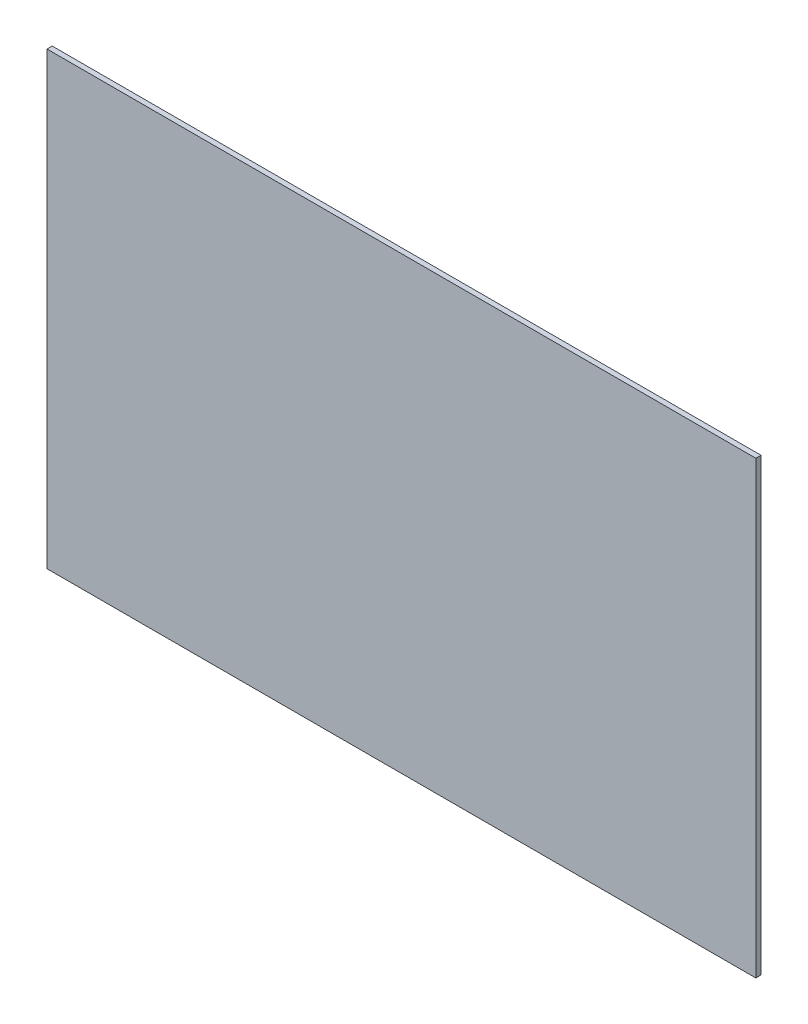
SolidWorks part; units mm, degrees
ref_plane "Plan de face" through (0, 0, 0) normal (0, 0, 1) x (1, 0, 0)
ref_plane "Plan de dessus" through (0, 0, 0) normal (0, 1, 0) x (1, 0, 0)
ref_plane "Plan de droite" through (0, 0, 0) normal (1, 0, 0) x (0, 0, -1)
sketch "Esquisse1" plane through (0, 0, 0) normal (0, 0, 1) x (1, 0, 0)
  line L1 (-274, -174) -> (274, -174)
  line L2 (-274, -174) -> (-274, 174)
  line L3 (-274, 174) -> (274, 174)
  line L4 (274, -174) -> (274, 174)
  line L5 (-274, -174) -> (274, 174) construction
  line L6 (-274, 174) -> (274, -174) construction
  point P0 (0, 0)
  dimension "D1" = 348
  dimension "D2" = 548
extrude "Boss.-Extru.1" add sketch "Esquisse1" along normal blind 4
sketch "Esquisse2" plane through (0, 0, 4) normal (0, 0, 1) x (1, 0, 0)
  line L0 (274, 174) -> (-274, 174) construction
  line L1 (-266, -166) -> (266, -166) construction
  line L2 (-266, -166) -> (-266, 166) construction
  line L3 (-266, 166) -> (266, 166) construction
  line L4 (266, -166) -> (266, 166) construction
  line L5 (-266, -166) -> (266, 166) construction
  line L6 (-266, 166) -> (266, -166) construction
  line L7 (-274, 174) -> (-274, -174) construction
  line L8 (274, -174) -> (274, 174) construction
  point P0 (124, 166)
  point P1 (-239, 166)
  point P2 (124, -166)
  point P3 (-239, -166)
  point P4 (0, 0)
  dimension "D1" = 8
  dimension "D2" = 8
  dimension "D3" = 35
  dimension "D4" = 150
hole_wizard "Dégagement M51" positions "Esquisse4" profile "Esquisse3" hole size "M5" standard "JIS"
sketch "Esquisse4" plane through (0, 0, 4) normal (0, 0, 1) x (1, 0, 0)
  point P0 (-140, -191.899)
  point P2 (-140, 191.9)
  point P4 (140, 188.1)
  point P6 (140, -191.9)
sketch "Esquisse3" plane through (-140, -191.899, 4) normal (1, 0, 0) x (0, -1, 0)
  line L0 (0, 0) -> (0, 4)
  line L1 (0, 4) -> (2.75, 4)
  line L2 (2.75, 4) -> (2.75, 0)
  line L5 (2.75, 0) -> (0, 0)
  line L11 (0, -6.35) -> (0, 107.95) construction
  dimension "Diamètre du perçage jusqu'au prochain" = 5.5
  dimension "Profondeur du perçage jusqu'au prochain" = 4
